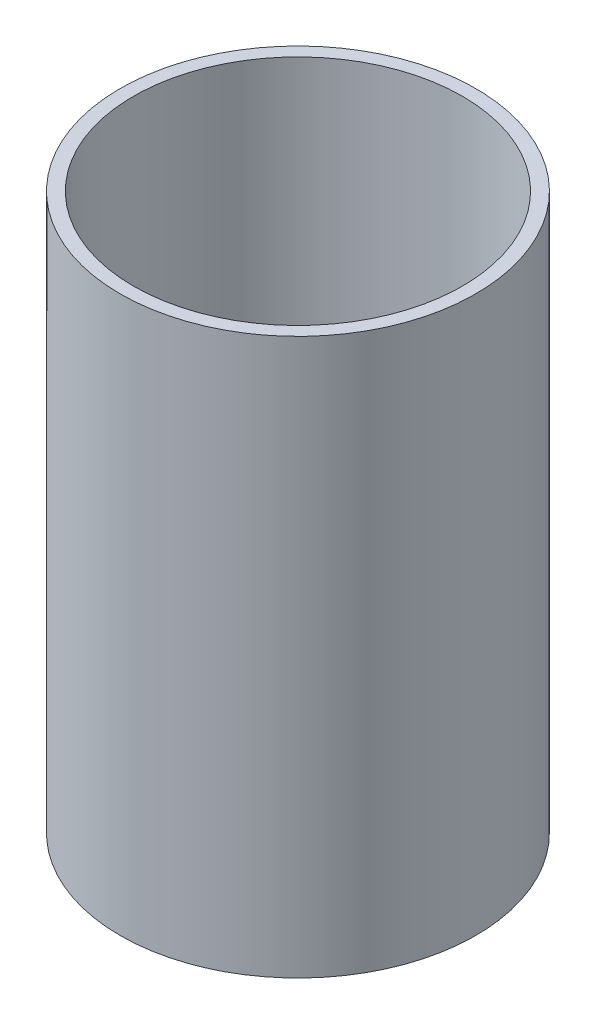
SolidWorks part; units mm, degrees
ref_plane "Front Plane" through (0, 0, 0) normal (0, 0, 1) x (1, 0, 0)
ref_plane "Top Plane" through (0, 0, 0) normal (0, 1, 0) x (1, 0, 0)
ref_plane "Right Plane" through (0, 0, 0) normal (1, 0, 0) x (0, 0, -1)
sketch "Sketch1" plane through (0, 0, 0) normal (0, 1, 0) x (1, 0, 0)
  circle A0 centre (0, 0) radius 16
  circle A1 centre (0, 0) radius 14.8
  dimension "D1" = 1.2
  dimension "D2" = 32
extrude "Boss-Extrude1" add sketch "Sketch1" along normal blind 50
